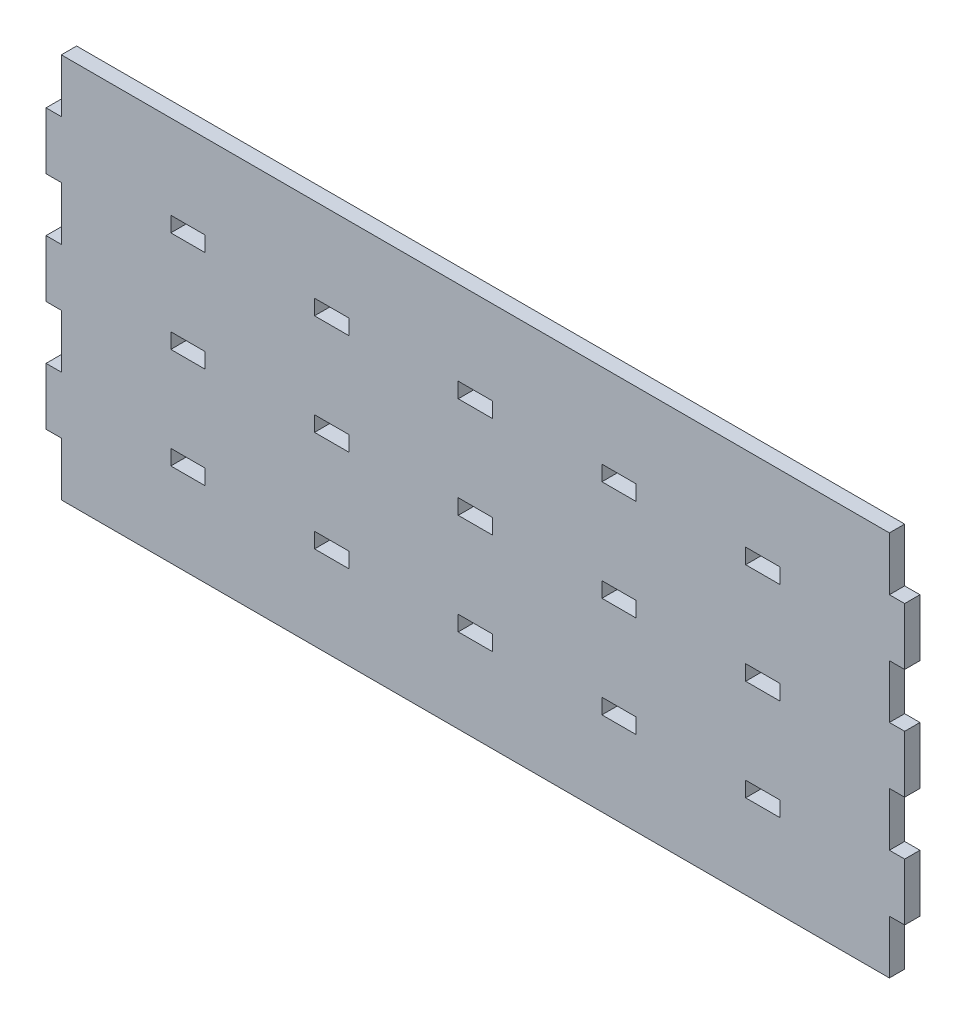
SolidWorks part; units mm, degrees
ref_plane "Front Plane" through (0, 0, 0) normal (0, 0, 1) x (1, 0, 0)
ref_plane "Top Plane" through (0, 0, 0) normal (0, 1, 0) x (1, 0, 0)
ref_plane "Right Plane" through (0, 0, 0) normal (1, 0, 0) x (0, 0, -1)
sketch "Model" plane through (0, 0, 0) normal (0, 0, 1) x (1, 0, 0)
  line L88 (0, 116.25) -> (0, 135)
  line L89 (0, 0) -> (290, 0)
  line L90 (0, 0) -> (0, 18.75)
  line L91 (0, 135) -> (290, 135)
  line L92 (290, 0) -> (290, 18.75)
  line L93 (0, 116.25) -> (-5.35, 116.25)
  line L94 (0, 77.5) -> (0, 96.25)
  line L95 (0, 96.25) -> (-5.35, 96.25)
  line L96 (-5.35, 116.25) -> (-5.35, 96.25)
  line L97 (0, 77.5) -> (-5.35, 77.5)
  line L98 (0, 38.75) -> (0, 57.5)
  line L99 (0, 57.5) -> (-5.35, 57.5)
  line L100 (-5.35, 77.5) -> (-5.35, 57.5)
  line L101 (0, 38.75) -> (-5.35, 38.75)
  line L102 (145, 0) -> (145, 135) construction
  line L103 (0, 18.75) -> (-5.35, 18.75)
  line L104 (-5.35, 38.75) -> (-5.35, 18.75)
  line L105 (295.35, 38.75) -> (295.35, 18.75)
  line L106 (290, 18.75) -> (295.35, 18.75)
  line L107 (290, 38.75) -> (295.35, 38.75)
  line L108 (295.35, 77.5) -> (295.35, 57.5)
  line L109 (290, 57.5) -> (295.35, 57.5)
  line L110 (290, 77.5) -> (295.35, 77.5)
  line L111 (295.35, 116.25) -> (295.35, 96.25)
  line L112 (290, 96.25) -> (295.35, 96.25)
  line L113 (290, 116.25) -> (295.35, 116.25)
  line L114 (290, 116.25) -> (290, 135)
  line L115 (290, 77.5) -> (290, 96.25)
  line L116 (290, 38.75) -> (290, 57.5)
  line L117 (189.33, 100.175) -> (201.33, 100.175)
  line L118 (139, 100.175) -> (151, 100.175)
  line L119 (139, 100.175) -> (139, 105.525)
  line L120 (139, 105.525) -> (151, 105.525)
  line L121 (151, 100.175) -> (151, 105.525)
  line L122 (139, 100.175) -> (151, 105.525) construction
  line L123 (139, 105.525) -> (151, 100.175) construction
  line L124 (189.33, 100.175) -> (189.33, 105.525)
  line L125 (189.33, 105.525) -> (201.33, 105.525)
  line L126 (201.33, 100.175) -> (201.33, 105.525)
  line L127 (189.33, 100.175) -> (201.33, 105.525) construction
  line L128 (189.33, 105.525) -> (201.33, 100.175) construction
  line L129 (239.66, 100.175) -> (251.66, 100.175)
  line L130 (239.66, 100.175) -> (239.66, 105.525)
  line L131 (239.66, 105.525) -> (251.66, 105.525)
  line L132 (251.66, 100.175) -> (251.66, 105.525)
  line L133 (239.66, 100.175) -> (251.66, 105.525) construction
  line L134 (239.66, 105.525) -> (251.66, 100.175) construction
  line L135 (189.33, 64.825) -> (201.33, 64.825)
  line L136 (189.33, 64.825) -> (189.33, 70.175)
  line L137 (189.33, 70.175) -> (201.33, 70.175)
  line L138 (201.33, 64.825) -> (201.33, 70.175)
  line L139 (189.33, 64.825) -> (201.33, 70.175) construction
  line L140 (189.33, 70.175) -> (201.33, 64.825) construction
  line L141 (239.66, 64.825) -> (251.66, 64.825)
  line L142 (239.66, 64.825) -> (239.66, 70.175)
  line L143 (239.66, 70.175) -> (251.66, 70.175)
  line L144 (251.66, 64.825) -> (251.66, 70.175)
  line L145 (239.66, 64.825) -> (251.66, 70.175) construction
  line L146 (239.66, 70.175) -> (251.66, 64.825) construction
  line L147 (189.33, 29.475) -> (201.33, 29.475)
  line L148 (189.33, 29.475) -> (189.33, 34.825)
  line L149 (189.33, 34.825) -> (201.33, 34.825)
  line L150 (201.33, 29.475) -> (201.33, 34.825)
  line L151 (189.33, 29.475) -> (201.33, 34.825) construction
  line L152 (189.33, 34.825) -> (201.33, 29.475) construction
  line L153 (239.66, 29.475) -> (251.66, 29.475)
  line L154 (239.66, 29.475) -> (239.66, 34.825)
  line L155 (239.66, 34.825) -> (251.66, 34.825)
  line L156 (251.66, 29.475) -> (251.66, 34.825)
  line L157 (239.66, 29.475) -> (251.66, 34.825) construction
  line L158 (239.66, 34.825) -> (251.66, 29.475) construction
  line L159 (139, 64.825) -> (151, 64.825)
  line L160 (139, 64.825) -> (139, 70.175)
  line L161 (139, 70.175) -> (151, 70.175)
  line L162 (151, 64.825) -> (151, 70.175)
  line L163 (139, 64.825) -> (151, 70.175) construction
  line L164 (139, 70.175) -> (151, 64.825) construction
  line L165 (139, 29.475) -> (151, 29.475)
  line L166 (139, 29.475) -> (139, 34.825)
  line L167 (139, 34.825) -> (151, 34.825)
  line L168 (151, 29.475) -> (151, 34.825)
  line L169 (139, 29.475) -> (151, 34.825) construction
  line L170 (139, 34.825) -> (151, 29.475) construction
  line L171 (88.67, 100.175) -> (100.67, 100.175)
  line L172 (88.67, 100.175) -> (88.67, 105.525)
  line L173 (88.67, 105.525) -> (100.67, 105.525)
  line L174 (100.67, 100.175) -> (100.67, 105.525)
  line L175 (88.67, 100.175) -> (100.67, 105.525) construction
  line L176 (88.67, 105.525) -> (100.67, 100.175) construction
  line L177 (38.34, 100.175) -> (50.34, 100.175)
  line L178 (38.34, 100.175) -> (38.34, 105.525)
  line L179 (38.34, 105.525) -> (50.34, 105.525)
  line L180 (50.34, 100.175) -> (50.34, 105.525)
  line L181 (38.34, 100.175) -> (50.34, 105.525) construction
  line L182 (38.34, 105.525) -> (50.34, 100.175) construction
  line L183 (88.67, 64.825) -> (100.67, 64.825)
  line L184 (88.67, 64.825) -> (88.67, 70.175)
  line L185 (88.67, 70.175) -> (100.67, 70.175)
  line L186 (100.67, 64.825) -> (100.67, 70.175)
  line L187 (88.67, 64.825) -> (100.67, 70.175) construction
  line L188 (88.67, 70.175) -> (100.67, 64.825) construction
  line L189 (38.34, 64.825) -> (50.34, 64.825)
  line L190 (38.34, 64.825) -> (38.34, 70.175)
  line L191 (38.34, 70.175) -> (50.34, 70.175)
  line L192 (50.34, 64.825) -> (50.34, 70.175)
  line L193 (38.34, 64.825) -> (50.34, 70.175) construction
  line L194 (38.34, 70.175) -> (50.34, 64.825) construction
  line L195 (88.67, 29.475) -> (100.67, 29.475)
  line L196 (88.67, 29.475) -> (88.67, 34.825)
  line L197 (88.67, 34.825) -> (100.67, 34.825)
  line L198 (100.67, 29.475) -> (100.67, 34.825)
  line L199 (88.67, 29.475) -> (100.67, 34.825) construction
  line L200 (88.67, 34.825) -> (100.67, 29.475) construction
  line L201 (38.34, 29.475) -> (50.34, 29.475)
  line L202 (38.34, 29.475) -> (38.34, 34.825)
  line L203 (38.34, 34.825) -> (50.34, 34.825)
  line L204 (50.34, 29.475) -> (50.34, 34.825)
  line L205 (38.34, 29.475) -> (50.34, 34.825) construction
  line L206 (38.34, 34.825) -> (50.34, 29.475) construction
  line L207 (139, 64.825) -> (151, 64.825) [skipped]
  line L208 (139, 64.825) -> (139, 70.175) [skipped]
  line L209 (139, 70.175) -> (151, 70.175) [skipped]
  line L210 (151, 64.825) -> (151, 70.175) [skipped]
  line L211 (139, 64.825) -> (151, 70.175) construction
  line L212 (139, 70.175) -> (151, 64.825) construction
  line L213 (139, 29.475) -> (151, 29.475) [skipped]
  line L214 (139, 29.475) -> (139, 34.825) [skipped]
  line L215 (139, 34.825) -> (151, 34.825) [skipped]
  line L216 (151, 29.475) -> (151, 34.825) [skipped]
  line L217 (139, 29.475) -> (151, 34.825) construction
  line L218 (139, 34.825) -> (151, 29.475) construction
  point P30 (145, 102.85)
  point P38 (195.33, 102.85)
  point P43 (245.66, 102.85)
  point P48 (195.33, 67.5)
  point P53 (245.66, 67.5)
  point P58 (195.33, 32.15)
  point P63 (245.66, 32.15)
  point P68 (145, 67.5)
  point P73 (145, 32.15)
  point P78 (94.67, 102.85)
  point P83 (44.34, 102.85)
  point P88 (94.67, 67.5)
  point P93 (44.34, 67.5)
  point P98 (94.67, 32.15)
  point P103 (44.34, 32.15)
  point P197 (145, 67.5)
  point P202 (145, 32.15)
  dimension "D2" = 290
  dimension "D4" = 135
  dimension "D6" = 5.35
  dimension "D8" = 20
  dimension "D13" = 5.35
  dimension "D15" = 12
  dimension "D18" = 29.475
  dimension "D19" = 38.33
  dimension "D24" = 38.33
  dimension "D26" = 30
  dimension "D10" = 3
  dimension "D11" = 3
  dimension "D22" = 3
  dimension "D23" = 3
extrude "Boss-Extrude1" add sketch "Model" along normal blind 5.35
equation "\"mdfthick\"=5.35"
equation "\"D6@Model\"=\"mdfthick\""
equation "\"D13@Model\"=\"mdfthick\""
equation "\"D1@Boss-Extrude1\"=\"mdfthick\""
